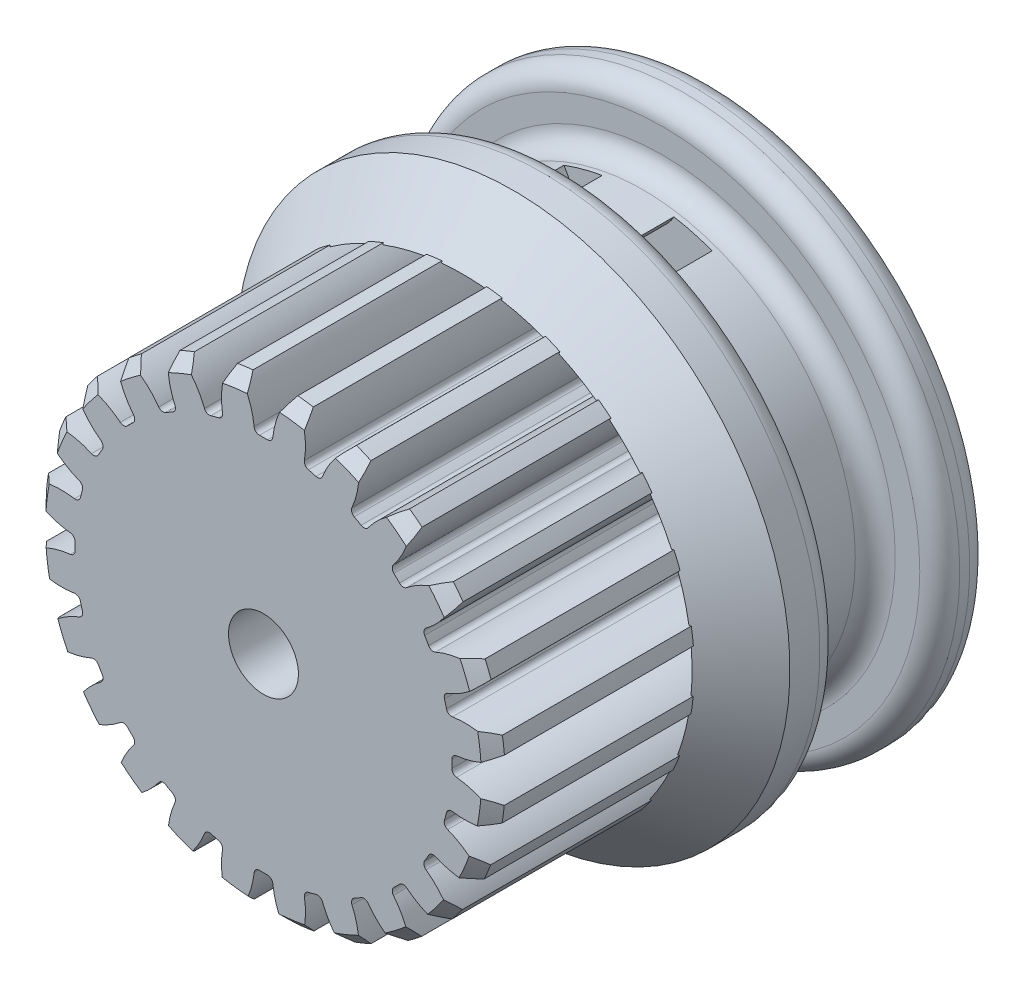
SolidWorks part; units mm, degrees
ref_plane "Plan de face" through (0, 0, 0) normal (0, 0, 1) x (1, 0, 0)
ref_plane "Plan de dessus" through (0, 0, 0) normal (0, 1, 0) x (1, 0, 0)
ref_plane "Plan de droite" through (0, 0, 0) normal (1, 0, 0) x (0, 0, -1)
sketch "Sketch1" plane through (0, 0, 0) normal (0, 0, 1) x (1, 0, 0)
  circle A0 centre (0, 0) radius 21.25 construction
  circle A1 centre (0, 0) radius 23.0208
  dimension "D1" = 42.5
  dimension "D2" = 46.0417
extrude "Boss-Extrude1" add sketch "Sketch1" along normal mid plane 25
sketch "Sketch2" plane through (0, 0, 12.5) normal (0, 0, 1) x (1, 0, 0)
  line L0 (0, 23.0208) -> (0, 0) construction
  line L1 (0, 0) -> (5.9582, 22.2364) construction
  line L2 (0, 0) -> (3.0048, 22.8239) construction
  line L3 (-0.8962, 18.7494) -> (0, 0) construction
  line L4 (-1.3898, 21.2045) -> (1.3898, 21.2045) construction
  line L5 (1.3898, 21.2045) -> (4.1457, 20.8417) construction
  line L6 (-2.0186, 22.9322) -> (0, 17.386) construction
  arc A0 (0.8962, 18.7494) -> (-0.8962, 18.7494) centre (0, 0) ccw
  circle A1 centre (0, 0) radius 19.4792 construction
  circle A2 centre (0, 0) radius 23.0208 construction
  arc A3 (2.2433, 22.9113) -> (0.8962, 18.7494) centre (9.2295, 18.3511) ccw
  arc A4 (-2.2433, 22.9113) -> (-0.8962, 18.7494) centre (-9.2295, 18.3511) cw
  circle A5 centre (0, 0) radius 23.0208 construction
  circle A6 centre (0, 0) radius 21.25 construction
  arc A7 (-2.2433, 22.9113) -> (2.2433, 22.9113) centre (0, 0) cw
  dimension "D1" = 15
  dimension "D2" = 3.5417
  dimension "D3" = 4.25
  dimension "D4" = 20
extrude "Cut-Extrude1" cut sketch "Sketch2" against normal through all
fillet "Fillet1" radius 0.5312 2 edges at (0.8962, 18.7494, 0) (-0.8962, 18.7494, 0)
chamfer "Chamfer1" distance 1.2 1 edges at (0, -23.0208, 12.5)
pattern_circular "CirPattern2" count 24 over 360 about axis through (0, -0.0957, 0) along (0, 0, 1) of "Fillet1", "Cut-Extrude1"
sketch "Sketch4" plane through (0, 0, 0) normal (1, 0, 0) x (0, 0, -1)
  line L2 (12.5, 27.707) -> (17.5, 27.707)
  line L3 (17.5, 27.707) -> (17.5, 21.25)
  line L4 (17.5, 21.25) -> (27.5, 21.25)
  line L5 (27.5, 21.25) -> (27.5, 27.707)
  line L6 (27.5, 27.707) -> (32.5, 27.707)
  line L7 (32.5, 27.707) -> (32.5, 0)
  line L8 (32.5, 0) -> (12.5, 0)
  line L9 (12.5, 0) -> (12.5, 22.9113)
  line L10 (12.5, 22.9113) -> (7.5, 22.9113)
  line L11 (12.5, 22.707) -> (-11.3, 22.707) construction
  line L12 (12.5, 22.9113) -> (-11.3, 22.9113) construction
  line L13 (7.5, 22.9113) -> (12.5, 27.707)
  dimension "D1" = 20
  dimension "D2" = 5
  dimension "D3" = 5
  dimension "D4" = 21.25
  dimension "D5" = 5
  dimension "D6" = 5
  dimension "D7" = 10
revolve "Revolve1" add sketch "Sketch4" angle 360 about L8
fillet "Fillet2" radius 2 5 edges at (-27.707, 0, -17.5) (-21.25, 0, -17.5) (-21.25, 0, -27.5) (-27.707, 0, -27.5) (-27.707, 0, -32.5)
sketch "Sketch5" plane through (0, 0, -32.5) normal (0, 0, -1) x (-1, 0, 0)
  circle A0 centre (0, 0) radius 7
  dimension "D1" = 14
extrude "Boss-Extrude3" add sketch "Sketch5" along normal blind 10
sketch "Sketch6" plane through (0, 0, -42.5) normal (0, 0, -1) x (-1, 0, 0)
  circle A0 centre (0, 0) radius 3.5
  dimension "D1" = 7
extrude "Cut-Extrude2" cut sketch "Sketch6" against normal through all
sketch "Sketch7" plane through (0, 0, 0) normal (1, 0, 0) x (0, 0, -1)
  line L0 (32.5, 0) -> (42.5, 0) construction
  line L1 (32.5, -7) -> (32.5, 7) construction
  line L2 (42.5, -7) -> (42.5, 7) construction
  circle A1 centre (37.5, 0) radius 1.725
  point P9 (37.5, 0)
  dimension "D1" = 3.45
extrude "Cut-Extrude3" cut sketch "Sketch7" against normal blind 10
sketch "Sketch8" plane through (0, 0, 0) normal (0, 0, 1) x (1, 0, 0)
  line L0 (0, 0) -> (0, 27.707) construction
  circle A0 centre (0, 0) radius 21.25 construction
  arc A1 (-7.4207, 19.9122) -> (-3.5898, 20.9446) centre (0, 0) cw
  arc A2 (-7.4207, 19.9122) -> (7.4207, 19.9122) centre (0, 23.5764) ccw
  arc A3 (7.4207, 19.9122) -> (3.5898, 20.9446) centre (0, 0) ccw
  arc A4 (3.5898, 20.9446) -> (-3.5898, 20.9446) centre (0, 22.8372) cw
  point P10 (0, 18.779)
  point P14 (0, 15.3003)
  point P15 (0, 0)
extrude "Cut-Extrude4" cut sketch "Sketch8" against normal blind 5 from offset 20 offset against normal yes
ref_plane "Plane1" through (0, 0, -22.5) normal (0, 0, 1) x (1, 0, 0)
equation "\"Module\"= ( 4.25 / \"Number of teeth\" )"
equation "\"Number of teeth\"= 24"
equation "\"Pressure angle\"= 20"
equation "\"D1@Sketch1\"=\"Module\" * \"Number of teeth\""
equation "\"D2@Sketch1\"=(\"Number of teeth\" + 2) * \"Module\""
equation "\"D2@Sketch2\"=\"Module\"*2"
equation "\"D1@Fillet1\"=0.3*\"Module\""
equation "\"D3@Sketch2\"=\"Module\"*2.4"
equation "\"D4@Sketch2\"=\"Pressure angle\""
equation "\"D1@Sketch2\"=360/\"Number of teeth\""
equation "\"D1@CirPattern2\"=\"Number of teeth\""
